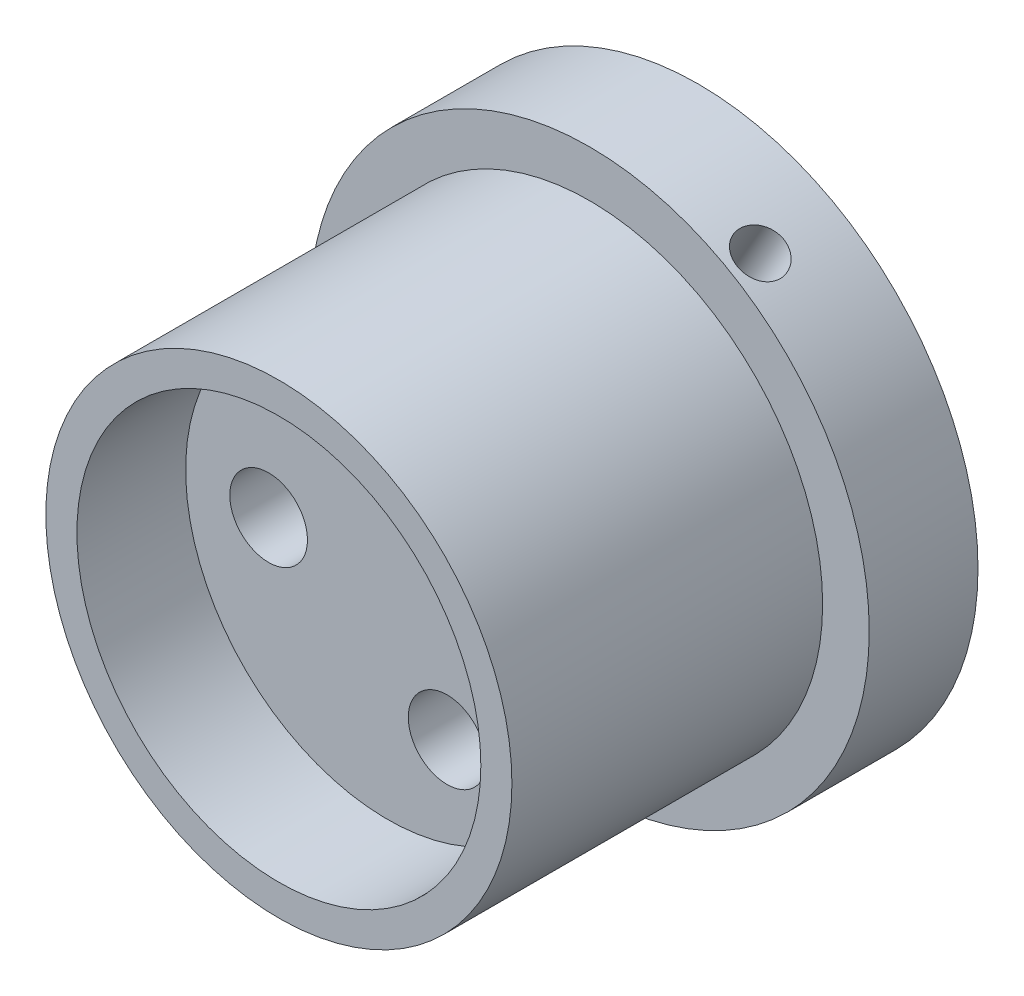
SolidWorks part; units mm, degrees
ref_plane "Front Plane" through (0, 0, 0) normal (0, 0, 1) x (1, 0, 0)
ref_plane "Top Plane" through (0, 0, 0) normal (0, 1, 0) x (1, 0, 0)
ref_plane "Right Plane" through (0, 0, 0) normal (1, 0, 0) x (0, 0, -1)
sketch "Sketch1" plane through (0, 0, 0) normal (0, 0, 1) x (1, 0, 0)
  circle A0 centre (0, 0) radius 15
  dimension "D1" = 30
extrude "Boss-Extrude1" add sketch "Sketch1" along normal blind 20
sketch "Sketch2" plane through (0, 0, 20) normal (0, 0, 1) x (1, 0, 0)
  circle A0 centre (0, 0) radius 10.95
  dimension "D1" = 21.9
extrude "Boss-Extrude2" add sketch "Sketch2" along normal blind 3.5 contours A0
sketch "Sketch4" plane through (0, 0, 0) normal (0, 0, -1) x (-1, 0, 0)
  circle A0 centre (0, 0) radius 3.05
  dimension "D1" = 6.1
extrude "Cut-Extrude1" cut sketch "Sketch4" against normal blind 4.1
sketch "Sketch5" plane through (0, 0, 4.1) normal (0, 0, -1) x (-1, 0, 0)
  circle A0 centre (0, 0) radius 1.5
  dimension "D1" = 3
extrude "Cut-Extrude2" cut sketch "Sketch5" along direction (0, 0, -1) on the side against the normal blind 4 contours A0
sketch "Sketch7" plane through (0, 0, 23.5) normal (0, 0, 1) x (1, 0, 0)
  circle A0 centre (0, 0) radius 3
  circle A1 centre (0, 0) radius 10.95
  dimension "D1" = 21.9
extrude "Boss-Extrude3" add sketch "Sketch7" along normal blind 11
sketch "Sketch9" plane through (0, 0, 34.5) normal (0, 0, 1) x (1, 0, 0)
  line L0 (0, 0) -> (7, 0) construction
  circle A0 centre (7, 0) radius 1.5
  circle A1 centre (-3.5, -6.0622) radius 1.5
  circle A2 centre (-3.5, 6.0622) radius 1.5
  dimension "D2" = 3
  dimension "D1" = 7
  dimension "D3" = 3
extrude "Cut-Extrude4" cut sketch "Sketch9" against normal through all
sketch "Sketch12" plane through (0, 0, 0) normal (0, 0, -1) x (-1, 0, 0)
  circle A0 centre (0, 0) radius 18
  circle A1 centre (3.5, 6.0622) radius 3.25
  circle A2 centre (3.5, -6.0622) radius 3.25
  circle A3 centre (-7, 0) radius 3.25
  circle A4 centre (0, 0) radius 3.05
  dimension "D1" = 36
extrude "Boss-Extrude4" add sketch "Sketch12" along normal blind 7
sketch "Sketch13" plane through (0, 0, 0) normal (1, 0, 0) x (0, 0, -1)
  line L0 (7, 0) -> (-3, 0) construction
  circle A0 centre (2, 0) radius 1.5
  dimension "D1" = 3
extrude "Cut-Extrude9" cut sketch "Sketch13" against normal blind 17 from offset 5 offset against normal yes
pattern_circular "CirPattern1" count 3 over 360 about axis through (0, 0, 0) along (0, 0, 1) of "Cut-Extrude9"
sketch "Sketch15" plane through (0, 0, 20) normal (0, 0, 1) x (1, 0, 0)
  circle A0 centre (0, 0) radius 13
  circle M2 centre (0, 0) radius 10.95
  dimension "D1" = 26
extrude "Cut-Extrude12" cut sketch "Sketch15" along normal blind 15 and the other way through all contours M2 | A0 M2
sketch "Sketch17" plane through (0, 0, 0) normal (0, 0, 1) x (1, 0, 0)
  circle A0 centre (0, 0) radius 13
extrude "Boss-Extrude6" add sketch "Sketch17" along normal blind 20 from offset 7 offset against normal yes
sketch "Sketch19" plane through (0, 0, -7) normal (0, 0, -1) x (-1, 0, 0)
  circle A0 centre (7.66, 0) radius 2.5
  circle A1 centre (-3.83, -6.6338) radius 2.5
  circle A2 centre (-3.83, 6.6338) radius 2.5
  dimension "D1" = 5
  dimension "D3" = 7.66
  dimension "D2" = 3
extrude "Cut-Extrude13" cut sketch "Sketch19" against normal through all
